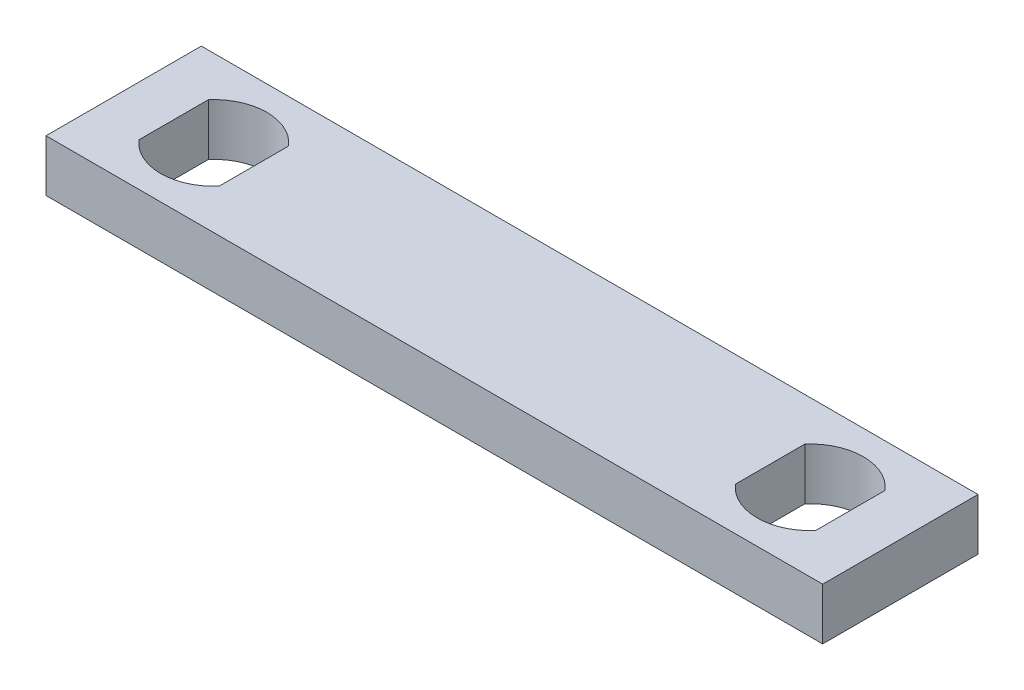
SolidWorks part; units mm, degrees
ref_plane "Front" through (0, 0, 0) normal (0, 0, 1) x (1, 0, 0)
ref_plane "Top" through (0, 0, 0) normal (0, 1, 0) x (1, 0, 0)
ref_plane "Right" through (0, 0, 0) normal (1, 0, 0) x (0, 0, -1)
sketch "Sketch1" plane through (0, 0, 0) normal (0, 1, 0) x (1, 0, 0)
  line L1 (-75, 15) -> (75, 15)
  line L2 (-75, 15) -> (-75, -15)
  line L3 (-75, -15) -> (75, -15)
  line L4 (75, 15) -> (75, -15)
  line L5 (-75, 15) -> (75, -15) construction
  line L6 (-75, -15) -> (75, 15) construction
  point P0 (0, 0)
  dimension "D1" = 30
  dimension "D2" = 150
extrude "Boss-Extrude1" add sketch "Sketch1" along normal mid plane 10
sketch "Sketch2" plane through (0, 5, 0) normal (0, 1, 0) x (1, 0, 0)
  line L0 (-65.35, 6.7082) -> (-65.35, -6.7082)
  line L1 (-49.85, 6.7082) -> (-49.85, -6.7082)
  arc A0 (-49.85, 6.7082) -> (-65.35, 6.7082) centre (-57.6, 0) ccw
  arc A1 (-65.35, -6.7082) -> (-49.85, -6.7082) centre (-57.6, 0) ccw
  point P6 (0, 0)
  point P7 (0, 0)
  dimension "D1" = 20.5
  dimension "D2" = 15.5
  dimension "D3" = 57.6
extrude "Cut-Extrude1" cut sketch "Sketch2" against normal through all
mirror "Mirror1" about plane through (0, 0, 0) normal (1, 0, 0) of "Cut-Extrude1"
